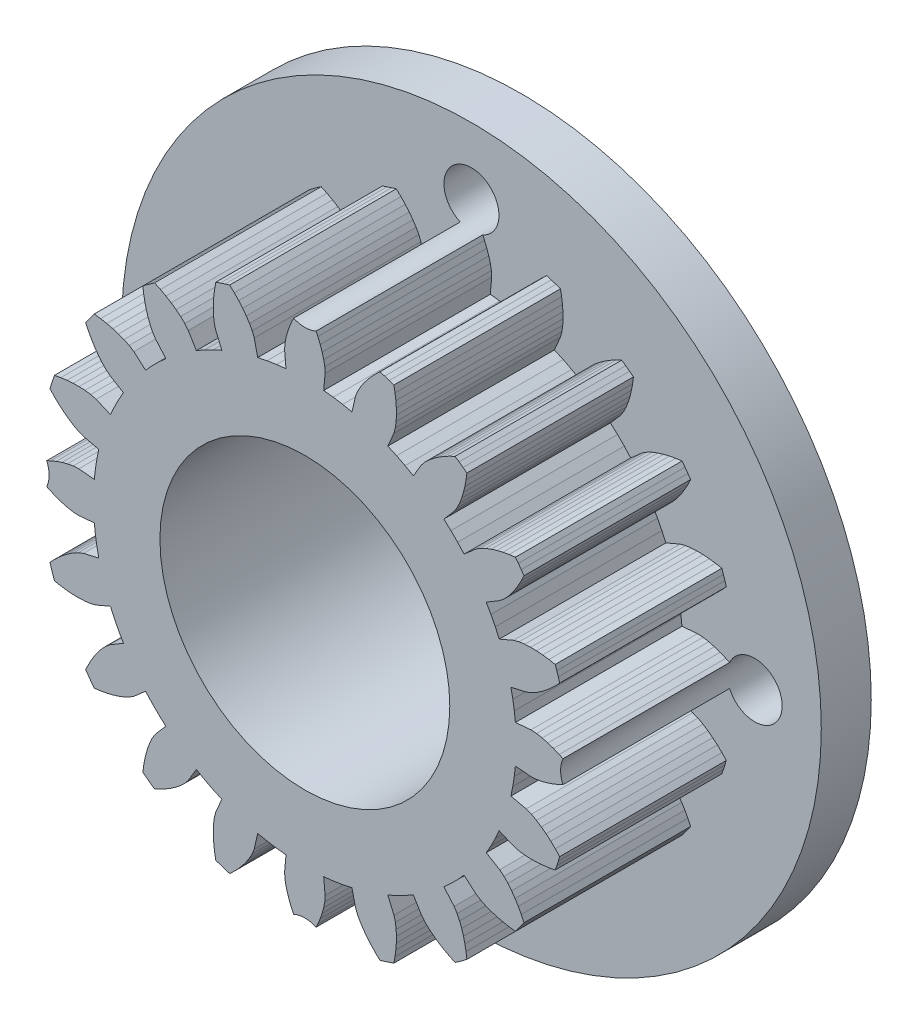
SolidWorks part; units mm, degrees
ref_plane "Спереди" through (0, 0, 0) normal (0, 0, 1) x (1, 0, 0)
ref_plane "Сверху" through (0, 0, 0) normal (0, 1, 0) x (1, 0, 0)
ref_plane "Справа" through (0, 0, 0) normal (1, 0, 0) x (0, 0, -1)
sketch "Эскиз1" plane through (0, 0, 0) normal (0, 0, 1) x (1, 0, 0)
  line L0 (12.6369, -1.1316) -> (13.5712, -1.2152)
  line L1 (13.5712, -1.2152) -> (13.9063, -1.1955)
  line L2 (13.9063, -1.1955) -> (14.2447, -1.1331)
  line L3 (14.2447, -1.1331) -> (14.5846, -1.0409)
  line L4 (14.5846, -1.0409) -> (14.9253, -0.9234)
  line L5 (14.9253, -0.9234) -> (15.2658, -0.7828)
  line L6 (15.2658, -0.7828) -> (15.6056, -0.6206)
  line L7 (15.6056, -0.6206) -> (15.944, -0.4377)
  line L8 (15.944, -0.4377) -> (15.9493, -0.1459)
  line L9 (15.9493, -0.1459) -> (15.9493, 0.1459)
  line L10 (15.9493, 0.1459) -> (15.944, 0.4377)
  line L11 (15.944, 0.4377) -> (15.6056, 0.6206)
  line L12 (15.6056, 0.6206) -> (15.2658, 0.7828)
  line L13 (15.2658, 0.7828) -> (14.9253, 0.9234)
  line L14 (14.9253, 0.9234) -> (14.5846, 1.0409)
  line L15 (14.5846, 1.0409) -> (14.2447, 1.1331)
  line L16 (14.2447, 1.1331) -> (13.9063, 1.1955)
  line L17 (13.9063, 1.1955) -> (13.5712, 1.2152)
  line L18 (13.5712, 1.2152) -> (12.6369, 1.1316)
  line L19 (12.6369, 1.1316) -> (12.5729, 1.7012)
  line L20 (12.5729, 1.7012) -> (12.4833, 2.2673)
  line L21 (12.4833, 2.2673) -> (12.3681, 2.8288)
  line L22 (12.3681, 2.8288) -> (13.2825, 3.038)
  line L23 (13.2825, 3.038) -> (13.5951, 3.1603)
  line L24 (13.5951, 3.1603) -> (13.8976, 3.3242)
  line L25 (13.8976, 3.3242) -> (14.1925, 3.5169)
  line L26 (14.1925, 3.5169) -> (14.4801, 3.7339)
  line L27 (14.4801, 3.7339) -> (14.7606, 3.9729)
  line L28 (14.7606, 3.9729) -> (15.0336, 4.2322)
  line L29 (15.0336, 4.2322) -> (15.2989, 4.5107)
  line L30 (15.2989, 4.5107) -> (15.2138, 4.7898)
  line L31 (15.2138, 4.7898) -> (15.1236, 5.0674)
  line L32 (15.1236, 5.0674) -> (15.0284, 5.3433)
  line L33 (15.0284, 5.3433) -> (14.65, 5.4126)
  line L34 (14.65, 5.4126) -> (14.2767, 5.4619)
  line L35 (14.2767, 5.4619) -> (13.9094, 5.4904)
  line L36 (13.9094, 5.4904) -> (13.5491, 5.4969)
  line L37 (13.5491, 5.4969) -> (13.1974, 5.4795)
  line L38 (13.1974, 5.4795) -> (12.8563, 5.4343)
  line L39 (12.8563, 5.4343) -> (12.5315, 5.3495)
  line L40 (12.5315, 5.3495) -> (11.6688, 4.9812)
  line L41 (11.6688, 4.9812) -> (11.4319, 5.5032)
  line L42 (11.4319, 5.5032) -> (11.1716, 6.0139)
  line L43 (11.1716, 6.0139) -> (10.8886, 6.5123)
  line L44 (10.8886, 6.5123) -> (11.6937, 6.9938)
  line L45 (11.6937, 6.9938) -> (11.9531, 7.2067)
  line L46 (11.9531, 7.2067) -> (12.1902, 7.4561)
  line L47 (12.1902, 7.4561) -> (12.4111, 7.7305)
  line L48 (12.4111, 7.7305) -> (12.6176, 8.0258)
  line L49 (12.6176, 8.0258) -> (12.8104, 8.3397)
  line L50 (12.8104, 8.3397) -> (12.99, 8.6707)
  line L51 (12.99, 8.6707) -> (13.1563, 9.0175)
  line L52 (13.1563, 9.0175) -> (12.9891, 9.2567)
  line L53 (12.9891, 9.2567) -> (12.8175, 9.4928)
  line L54 (12.8175, 9.4928) -> (12.6417, 9.7258)
  line L55 (12.6417, 9.7258) -> (12.2604, 9.6748)
  line L56 (12.2604, 9.6748) -> (11.8902, 9.6063)
  line L57 (11.8902, 9.6063) -> (11.532, 9.5199)
  line L58 (11.532, 9.5199) -> (11.1874, 9.4148)
  line L59 (11.1874, 9.4148) -> (10.8582, 9.2895)
  line L60 (10.8582, 9.2895) -> (10.5477, 9.1411)
  line L61 (10.5477, 9.1411) -> (10.2651, 8.9601)
  line L62 (10.2651, 8.9601) -> (9.5584, 8.3433)
  line L63 (9.5584, 8.3433) -> (9.1718, 8.7665)
  line L64 (9.1718, 8.7665) -> (8.7665, 9.1718)
  line L65 (8.7665, 9.1718) -> (8.3433, 9.5584)
  line L66 (8.3433, 9.5584) -> (8.9601, 10.2651)
  line L67 (8.9601, 10.2651) -> (9.1411, 10.5477)
  line L68 (9.1411, 10.5477) -> (9.2895, 10.8582)
  line L69 (9.2895, 10.8582) -> (9.4148, 11.1874)
  line L70 (9.4148, 11.1874) -> (9.5199, 11.532)
  line L71 (9.5199, 11.532) -> (9.6063, 11.8902)
  line L72 (9.6063, 11.8902) -> (9.6748, 12.2604)
  line L73 (9.6748, 12.2604) -> (9.7258, 12.6417)
  line L74 (9.7258, 12.6417) -> (9.4928, 12.8175)
  line L75 (9.4928, 12.8175) -> (9.2567, 12.9891)
  line L76 (9.2567, 12.9891) -> (9.0175, 13.1563)
  line L77 (9.0175, 13.1563) -> (8.6707, 12.99)
  line L78 (8.6707, 12.99) -> (8.3397, 12.8104)
  line L79 (8.3397, 12.8104) -> (8.0258, 12.6176)
  line L80 (8.0258, 12.6176) -> (7.7305, 12.4111)
  line L81 (7.7305, 12.4111) -> (7.4561, 12.1902)
  line L82 (7.4561, 12.1902) -> (7.2067, 11.9531)
  line L83 (7.2067, 11.9531) -> (6.9938, 11.6937)
  line L84 (6.9938, 11.6937) -> (6.5123, 10.8886)
  line L85 (6.5123, 10.8886) -> (6.0139, 11.1716)
  line L86 (6.0139, 11.1716) -> (5.5032, 11.4319)
  line L87 (5.5032, 11.4319) -> (4.9812, 11.6688)
  line L88 (4.9812, 11.6688) -> (5.3495, 12.5315)
  line L89 (5.3495, 12.5315) -> (5.4343, 12.8563)
  line L90 (5.4343, 12.8563) -> (5.4795, 13.1974)
  line L91 (5.4795, 13.1974) -> (5.4969, 13.5491)
  line L92 (5.4969, 13.5491) -> (5.4904, 13.9094)
  line L93 (5.4904, 13.9094) -> (5.4619, 14.2767)
  line L94 (5.4619, 14.2767) -> (5.4126, 14.65)
  line L95 (5.4126, 14.65) -> (5.3433, 15.0284)
  line L96 (5.3433, 15.0284) -> (5.0674, 15.1236)
  line L97 (5.0674, 15.1236) -> (4.7898, 15.2138)
  line L98 (4.7898, 15.2138) -> (4.5107, 15.2989)
  line L99 (4.5107, 15.2989) -> (4.2322, 15.0336)
  line L100 (4.2322, 15.0336) -> (3.9729, 14.7606)
  line L101 (3.9729, 14.7606) -> (3.7339, 14.4801)
  line L102 (3.7339, 14.4801) -> (3.5169, 14.1925)
  line L103 (3.5169, 14.1925) -> (3.3242, 13.8976)
  line L104 (3.3242, 13.8976) -> (3.1603, 13.5951)
  line L105 (3.1603, 13.5951) -> (3.038, 13.2825)
  line L106 (3.038, 13.2825) -> (2.8288, 12.3681)
  line L107 (2.8288, 12.3681) -> (2.2673, 12.4833)
  line L108 (2.2673, 12.4833) -> (1.7012, 12.5729)
  line L109 (1.7012, 12.5729) -> (1.1316, 12.6369)
  line L110 (1.1316, 12.6369) -> (1.2152, 13.5712)
  line L111 (1.2152, 13.5712) -> (1.1955, 13.9063)
  line L112 (1.1955, 13.9063) -> (1.1331, 14.2447)
  line L113 (1.1331, 14.2447) -> (1.0409, 14.5846)
  line L114 (1.0409, 14.5846) -> (0.9234, 14.9253)
  line L115 (0.9234, 14.9253) -> (0.7828, 15.2658)
  line L116 (0.7828, 15.2658) -> (0.6206, 15.6056)
  line L117 (0.6206, 15.6056) -> (0.4377, 15.944)
  line L118 (0.4377, 15.944) -> (0.1459, 15.9493)
  line L119 (0.1459, 15.9493) -> (-0.1459, 15.9493)
  line L120 (-0.1459, 15.9493) -> (-0.4377, 15.944)
  line L121 (-0.4377, 15.944) -> (-0.6206, 15.6056)
  line L122 (-0.6206, 15.6056) -> (-0.7828, 15.2658)
  line L123 (-0.7828, 15.2658) -> (-0.9234, 14.9253)
  line L124 (-0.9234, 14.9253) -> (-1.0409, 14.5846)
  line L125 (-1.0409, 14.5846) -> (-1.1331, 14.2447)
  line L126 (-1.1331, 14.2447) -> (-1.1955, 13.9063)
  line L127 (-1.1955, 13.9063) -> (-1.2152, 13.5712)
  line L128 (-1.2152, 13.5712) -> (-1.1316, 12.6369)
  line L129 (-1.1316, 12.6369) -> (-1.7012, 12.5729)
  line L130 (-1.7012, 12.5729) -> (-2.2673, 12.4833)
  line L131 (-2.2673, 12.4833) -> (-2.8288, 12.3681)
  line L132 (-2.8288, 12.3681) -> (-3.038, 13.2825)
  line L133 (-3.038, 13.2825) -> (-3.1603, 13.5951)
  line L134 (-3.1603, 13.5951) -> (-3.3242, 13.8976)
  line L135 (-3.3242, 13.8976) -> (-3.5169, 14.1925)
  line L136 (-3.5169, 14.1925) -> (-3.7339, 14.4801)
  line L137 (-3.7339, 14.4801) -> (-3.9729, 14.7606)
  line L138 (-3.9729, 14.7606) -> (-4.2322, 15.0336)
  line L139 (-4.2322, 15.0336) -> (-4.5107, 15.2989)
  line L140 (-4.5107, 15.2989) -> (-4.7898, 15.2138)
  line L141 (-4.7898, 15.2138) -> (-5.0674, 15.1236)
  line L142 (-5.0674, 15.1236) -> (-5.3433, 15.0284)
  line L143 (-5.3433, 15.0284) -> (-5.4126, 14.65)
  line L144 (-5.4126, 14.65) -> (-5.4619, 14.2767)
  line L145 (-5.4619, 14.2767) -> (-5.4904, 13.9094)
  line L146 (-5.4904, 13.9094) -> (-5.4969, 13.5491)
  line L147 (-5.4969, 13.5491) -> (-5.4795, 13.1974)
  line L148 (-5.4795, 13.1974) -> (-5.4343, 12.8563)
  line L149 (-5.4343, 12.8563) -> (-5.3495, 12.5315)
  line L150 (-5.3495, 12.5315) -> (-4.9812, 11.6688)
  line L151 (-4.9812, 11.6688) -> (-5.5032, 11.4319)
  line L152 (-5.5032, 11.4319) -> (-6.0139, 11.1716)
  line L153 (-6.0139, 11.1716) -> (-6.5123, 10.8886)
  line L154 (-6.5123, 10.8886) -> (-6.9938, 11.6937)
  line L155 (-6.9938, 11.6937) -> (-7.2067, 11.9531)
  line L156 (-7.2067, 11.9531) -> (-7.4561, 12.1902)
  line L157 (-7.4561, 12.1902) -> (-7.7305, 12.4111)
  line L158 (-7.7305, 12.4111) -> (-8.0258, 12.6176)
  line L159 (-8.0258, 12.6176) -> (-8.3397, 12.8104)
  line L160 (-8.3397, 12.8104) -> (-8.6707, 12.99)
  line L161 (-8.6707, 12.99) -> (-9.0175, 13.1563)
  line L162 (-9.0175, 13.1563) -> (-9.2567, 12.9891)
  line L163 (-9.2567, 12.9891) -> (-9.4928, 12.8175)
  line L164 (-9.4928, 12.8175) -> (-9.7258, 12.6417)
  line L165 (-9.7258, 12.6417) -> (-9.6748, 12.2604)
  line L166 (-9.6748, 12.2604) -> (-9.6063, 11.8902)
  line L167 (-9.6063, 11.8902) -> (-9.5199, 11.532)
  line L168 (-9.5199, 11.532) -> (-9.4148, 11.1874)
  line L169 (-9.4148, 11.1874) -> (-9.2895, 10.8582)
  line L170 (-9.2895, 10.8582) -> (-9.1411, 10.5477)
  line L171 (-9.1411, 10.5477) -> (-8.9601, 10.2651)
  line L172 (-8.9601, 10.2651) -> (-8.3433, 9.5584)
  line L173 (-8.3433, 9.5584) -> (-8.7665, 9.1718)
  line L174 (-8.7665, 9.1718) -> (-9.1718, 8.7665)
  line L175 (-9.1718, 8.7665) -> (-9.5584, 8.3433)
  line L176 (-9.5584, 8.3433) -> (-10.2651, 8.9601)
  line L177 (-10.2651, 8.9601) -> (-10.5477, 9.1411)
  line L178 (-10.5477, 9.1411) -> (-10.8582, 9.2895)
  line L179 (-10.8582, 9.2895) -> (-11.1874, 9.4148)
  line L180 (-11.1874, 9.4148) -> (-11.532, 9.5199)
  line L181 (-11.532, 9.5199) -> (-11.8902, 9.6063)
  line L182 (-11.8902, 9.6063) -> (-12.2604, 9.6748)
  line L183 (-12.2604, 9.6748) -> (-12.6417, 9.7258)
  line L184 (-12.6417, 9.7258) -> (-12.8175, 9.4928)
  line L185 (-12.8175, 9.4928) -> (-12.9891, 9.2567)
  line L186 (-12.9891, 9.2567) -> (-13.1563, 9.0175)
  line L187 (-13.1563, 9.0175) -> (-12.99, 8.6707)
  line L188 (-12.99, 8.6707) -> (-12.8104, 8.3397)
  line L189 (-12.8104, 8.3397) -> (-12.6176, 8.0258)
  line L190 (-12.6176, 8.0258) -> (-12.4111, 7.7305)
  line L191 (-12.4111, 7.7305) -> (-12.1902, 7.4561)
  line L192 (-12.1902, 7.4561) -> (-11.9531, 7.2067)
  line L193 (-11.9531, 7.2067) -> (-11.6937, 6.9938)
  line L194 (-11.6937, 6.9938) -> (-10.8886, 6.5123)
  line L195 (-10.8886, 6.5123) -> (-11.1716, 6.0139)
  line L196 (-11.1716, 6.0139) -> (-11.4319, 5.5032)
  line L197 (-11.4319, 5.5032) -> (-11.6688, 4.9812)
  line L198 (-11.6688, 4.9812) -> (-12.5315, 5.3495)
  line L199 (-12.5315, 5.3495) -> (-12.8563, 5.4343)
  line L200 (-12.8563, 5.4343) -> (-13.1974, 5.4795)
  line L201 (-13.1974, 5.4795) -> (-13.5491, 5.4969)
  line L202 (-13.5491, 5.4969) -> (-13.9094, 5.4904)
  line L203 (-13.9094, 5.4904) -> (-14.2767, 5.4619)
  line L204 (-14.2767, 5.4619) -> (-14.65, 5.4126)
  line L205 (-14.65, 5.4126) -> (-15.0284, 5.3433)
  line L206 (-15.0284, 5.3433) -> (-15.1236, 5.0674)
  line L207 (-15.1236, 5.0674) -> (-15.2138, 4.7898)
  line L208 (-15.2138, 4.7898) -> (-15.2989, 4.5107)
  line L209 (-15.2989, 4.5107) -> (-15.0336, 4.2322)
  line L210 (-15.0336, 4.2322) -> (-14.7606, 3.9729)
  line L211 (-14.7606, 3.9729) -> (-14.4801, 3.7339)
  line L212 (-14.4801, 3.7339) -> (-14.1925, 3.5169)
  line L213 (-14.1925, 3.5169) -> (-13.8976, 3.3242)
  line L214 (-13.8976, 3.3242) -> (-13.5951, 3.1603)
  line L215 (-13.5951, 3.1603) -> (-13.2825, 3.038)
  line L216 (-13.2825, 3.038) -> (-12.3681, 2.8288)
  line L217 (-12.3681, 2.8288) -> (-12.4833, 2.2673)
  line L218 (-12.4833, 2.2673) -> (-12.5729, 1.7012)
  line L219 (-12.5729, 1.7012) -> (-12.6369, 1.1316)
  line L220 (-12.6369, 1.1316) -> (-13.5712, 1.2152)
  line L221 (-13.5712, 1.2152) -> (-13.9063, 1.1955)
  line L222 (-13.9063, 1.1955) -> (-14.2447, 1.1331)
  line L223 (-14.2447, 1.1331) -> (-14.5846, 1.0409)
  line L224 (-14.5846, 1.0409) -> (-14.9253, 0.9234)
  line L225 (-14.9253, 0.9234) -> (-15.2658, 0.7828)
  line L226 (-15.2658, 0.7828) -> (-15.6056, 0.6206)
  line L227 (-15.6056, 0.6206) -> (-15.944, 0.4377)
  line L228 (-15.944, 0.4377) -> (-15.9493, 0.1459)
  line L229 (-15.9493, 0.1459) -> (-15.9493, -0.1459)
  line L230 (-15.9493, -0.1459) -> (-15.944, -0.4377)
  line L231 (-15.944, -0.4377) -> (-15.6056, -0.6206)
  line L232 (-15.6056, -0.6206) -> (-15.2658, -0.7828)
  line L233 (-15.2658, -0.7828) -> (-14.9253, -0.9234)
  line L234 (-14.9253, -0.9234) -> (-14.5846, -1.0409)
  line L235 (-14.5846, -1.0409) -> (-14.2447, -1.1331)
  line L236 (-14.2447, -1.1331) -> (-13.9063, -1.1955)
  line L237 (-13.9063, -1.1955) -> (-13.5712, -1.2152)
  line L238 (-13.5712, -1.2152) -> (-12.6369, -1.1316)
  line L239 (-12.6369, -1.1316) -> (-12.5729, -1.7012)
  line L240 (-12.5729, -1.7012) -> (-12.4833, -2.2673)
  line L241 (-12.4833, -2.2673) -> (-12.3681, -2.8288)
  line L242 (-12.3681, -2.8288) -> (-13.2825, -3.038)
  line L243 (-13.2825, -3.038) -> (-13.5951, -3.1603)
  line L244 (-13.5951, -3.1603) -> (-13.8976, -3.3242)
  line L245 (-13.8976, -3.3242) -> (-14.1925, -3.5169)
  line L246 (-14.1925, -3.5169) -> (-14.4801, -3.7339)
  line L247 (-14.4801, -3.7339) -> (-14.7606, -3.9729)
  line L248 (-14.7606, -3.9729) -> (-15.0336, -4.2322)
  line L249 (-15.0336, -4.2322) -> (-15.2989, -4.5107)
  line L250 (-15.2989, -4.5107) -> (-15.2138, -4.7898)
  line L251 (-15.2138, -4.7898) -> (-15.1236, -5.0674)
  line L252 (-15.1236, -5.0674) -> (-15.0284, -5.3433)
  line L253 (-15.0284, -5.3433) -> (-14.65, -5.4126)
  line L254 (-14.65, -5.4126) -> (-14.2767, -5.4619)
  line L255 (-14.2767, -5.4619) -> (-13.9094, -5.4904)
  line L256 (-13.9094, -5.4904) -> (-13.5491, -5.4969)
  line L257 (-13.5491, -5.4969) -> (-13.1974, -5.4795)
  line L258 (-13.1974, -5.4795) -> (-12.8563, -5.4343)
  line L259 (-12.8563, -5.4343) -> (-12.5315, -5.3495)
  line L260 (-12.5315, -5.3495) -> (-11.6688, -4.9812)
  line L261 (-11.6688, -4.9812) -> (-11.4319, -5.5032)
  line L262 (-11.4319, -5.5032) -> (-11.1716, -6.0139)
  line L263 (-11.1716, -6.0139) -> (-10.8886, -6.5123)
  line L264 (-10.8886, -6.5123) -> (-11.6937, -6.9938)
  line L265 (-11.6937, -6.9938) -> (-11.9531, -7.2067)
  line L266 (-11.9531, -7.2067) -> (-12.1902, -7.4561)
  line L267 (-12.1902, -7.4561) -> (-12.4111, -7.7305)
  line L268 (-12.4111, -7.7305) -> (-12.6176, -8.0258)
  line L269 (-12.6176, -8.0258) -> (-12.8104, -8.3397)
  line L270 (-12.8104, -8.3397) -> (-12.99, -8.6707)
  line L271 (-12.99, -8.6707) -> (-13.1563, -9.0175)
  line L272 (-13.1563, -9.0175) -> (-12.9891, -9.2567)
  line L273 (-12.9891, -9.2567) -> (-12.8175, -9.4928)
  line L274 (-12.8175, -9.4928) -> (-12.6417, -9.7258)
  line L275 (-12.6417, -9.7258) -> (-12.2604, -9.6748)
  line L276 (-12.2604, -9.6748) -> (-11.8902, -9.6063)
  line L277 (-11.8902, -9.6063) -> (-11.532, -9.5199)
  line L278 (-11.532, -9.5199) -> (-11.1874, -9.4148)
  line L279 (-11.1874, -9.4148) -> (-10.8582, -9.2895)
  line L280 (-10.8582, -9.2895) -> (-10.5477, -9.1411)
  line L281 (-10.5477, -9.1411) -> (-10.2651, -8.9601)
  line L282 (-10.2651, -8.9601) -> (-9.5584, -8.3433)
  line L283 (-9.5584, -8.3433) -> (-9.1718, -8.7665)
  line L284 (-9.1718, -8.7665) -> (-8.7665, -9.1718)
  line L285 (-8.7665, -9.1718) -> (-8.3433, -9.5584)
  line L286 (-8.3433, -9.5584) -> (-8.9601, -10.2651)
  line L287 (-8.9601, -10.2651) -> (-9.1411, -10.5477)
  line L288 (-9.1411, -10.5477) -> (-9.2895, -10.8582)
  line L289 (-9.2895, -10.8582) -> (-9.4148, -11.1874)
  line L290 (-9.4148, -11.1874) -> (-9.5199, -11.532)
  line L291 (-9.5199, -11.532) -> (-9.6063, -11.8902)
  line L292 (-9.6063, -11.8902) -> (-9.6748, -12.2604)
  line L293 (-9.6748, -12.2604) -> (-9.7258, -12.6417)
  line L294 (-9.7258, -12.6417) -> (-9.4928, -12.8175)
  line L295 (-9.4928, -12.8175) -> (-9.2567, -12.9891)
  line L296 (-9.2567, -12.9891) -> (-9.0175, -13.1563)
  line L297 (-9.0175, -13.1563) -> (-8.6707, -12.99)
  line L298 (-8.6707, -12.99) -> (-8.3397, -12.8104)
  line L299 (-8.3397, -12.8104) -> (-8.0258, -12.6176)
  line L300 (-8.0258, -12.6176) -> (-7.7305, -12.4111)
  line L301 (-7.7305, -12.4111) -> (-7.4561, -12.1902)
  line L302 (-7.4561, -12.1902) -> (-7.2067, -11.9531)
  line L303 (-7.2067, -11.9531) -> (-6.9938, -11.6937)
  line L304 (-6.9938, -11.6937) -> (-6.5123, -10.8886)
  line L305 (-6.5123, -10.8886) -> (-6.0139, -11.1716)
  line L306 (-6.0139, -11.1716) -> (-5.5032, -11.4319)
  line L307 (-5.5032, -11.4319) -> (-4.9812, -11.6688)
  line L308 (-4.9812, -11.6688) -> (-5.3495, -12.5315)
  line L309 (-5.3495, -12.5315) -> (-5.4343, -12.8563)
  line L310 (-5.4343, -12.8563) -> (-5.4795, -13.1974)
  line L311 (-5.4795, -13.1974) -> (-5.4969, -13.5491)
  line L312 (-5.4969, -13.5491) -> (-5.4904, -13.9094)
  line L313 (-5.4904, -13.9094) -> (-5.4619, -14.2767)
  line L314 (-5.4619, -14.2767) -> (-5.4126, -14.65)
  line L315 (-5.4126, -14.65) -> (-5.3433, -15.0284)
  line L316 (-5.3433, -15.0284) -> (-5.0674, -15.1236)
  line L317 (-5.0674, -15.1236) -> (-4.7898, -15.2138)
  line L318 (-4.7898, -15.2138) -> (-4.5107, -15.2989)
  line L319 (-4.5107, -15.2989) -> (-4.2322, -15.0336)
  line L320 (-4.2322, -15.0336) -> (-3.9729, -14.7606)
  line L321 (-3.9729, -14.7606) -> (-3.7339, -14.4801)
  line L322 (-3.7339, -14.4801) -> (-3.5169, -14.1925)
  line L323 (-3.5169, -14.1925) -> (-3.3242, -13.8976)
  line L324 (-3.3242, -13.8976) -> (-3.1603, -13.5951)
  line L325 (-3.1603, -13.5951) -> (-3.038, -13.2825)
  line L326 (-3.038, -13.2825) -> (-2.8288, -12.3681)
  line L327 (-2.8288, -12.3681) -> (-2.2673, -12.4833)
  line L328 (-2.2673, -12.4833) -> (-1.7012, -12.5729)
  line L329 (-1.7012, -12.5729) -> (-1.1316, -12.6369)
  line L330 (-1.1316, -12.6369) -> (-1.2152, -13.5712)
  line L331 (-1.2152, -13.5712) -> (-1.1955, -13.9063)
  line L332 (-1.1955, -13.9063) -> (-1.1331, -14.2447)
  line L333 (-1.1331, -14.2447) -> (-1.0409, -14.5846)
  line L334 (-1.0409, -14.5846) -> (-0.9234, -14.9253)
  line L335 (-0.9234, -14.9253) -> (-0.7828, -15.2658)
  line L336 (-0.7828, -15.2658) -> (-0.6206, -15.6056)
  line L337 (-0.6206, -15.6056) -> (-0.4377, -15.944)
  line L338 (-0.4377, -15.944) -> (-0.1459, -15.9493)
  line L339 (-0.1459, -15.9493) -> (0.1459, -15.9493)
  line L340 (0.1459, -15.9493) -> (0.4377, -15.944)
  line L341 (0.4377, -15.944) -> (0.6206, -15.6056)
  line L342 (0.6206, -15.6056) -> (0.7828, -15.2658)
  line L343 (0.7828, -15.2658) -> (0.9234, -14.9253)
  line L344 (0.9234, -14.9253) -> (1.0409, -14.5846)
  line L345 (1.0409, -14.5846) -> (1.1331, -14.2447)
  line L346 (1.1331, -14.2447) -> (1.1955, -13.9063)
  line L347 (1.1955, -13.9063) -> (1.2152, -13.5712)
  line L348 (1.2152, -13.5712) -> (1.1316, -12.6369)
  line L349 (1.1316, -12.6369) -> (1.7012, -12.5729)
  line L350 (1.7012, -12.5729) -> (2.2673, -12.4833)
  line L351 (2.2673, -12.4833) -> (2.8288, -12.3681)
  line L352 (2.8288, -12.3681) -> (3.038, -13.2825)
  line L353 (3.038, -13.2825) -> (3.1603, -13.5951)
  line L354 (3.1603, -13.5951) -> (3.3242, -13.8976)
  line L355 (3.3242, -13.8976) -> (3.5169, -14.1925)
  line L356 (3.5169, -14.1925) -> (3.7339, -14.4801)
  line L357 (3.7339, -14.4801) -> (3.9729, -14.7606)
  line L358 (3.9729, -14.7606) -> (4.2322, -15.0336)
  line L359 (4.2322, -15.0336) -> (4.5107, -15.2989)
  line L360 (4.5107, -15.2989) -> (4.7898, -15.2138)
  line L361 (4.7898, -15.2138) -> (5.0674, -15.1236)
  line L362 (5.0674, -15.1236) -> (5.3433, -15.0284)
  line L363 (5.3433, -15.0284) -> (5.4126, -14.65)
  line L364 (5.4126, -14.65) -> (5.4619, -14.2767)
  line L365 (5.4619, -14.2767) -> (5.4904, -13.9094)
  line L366 (5.4904, -13.9094) -> (5.4969, -13.5491)
  line L367 (5.4969, -13.5491) -> (5.4795, -13.1974)
  line L368 (5.4795, -13.1974) -> (5.4343, -12.8563)
  line L369 (5.4343, -12.8563) -> (5.3495, -12.5315)
  line L370 (5.3495, -12.5315) -> (4.9812, -11.6688)
  line L371 (4.9812, -11.6688) -> (5.5032, -11.4319)
  line L372 (5.5032, -11.4319) -> (6.0139, -11.1716)
  line L373 (6.0139, -11.1716) -> (6.5123, -10.8886)
  line L374 (6.5123, -10.8886) -> (6.9938, -11.6937)
  line L375 (6.9938, -11.6937) -> (7.2067, -11.9531)
  line L376 (7.2067, -11.9531) -> (7.4561, -12.1902)
  line L377 (7.4561, -12.1902) -> (7.7305, -12.4111)
  line L378 (7.7305, -12.4111) -> (8.0258, -12.6176)
  line L379 (8.0258, -12.6176) -> (8.3397, -12.8104)
  line L380 (8.3397, -12.8104) -> (8.6707, -12.99)
  line L381 (8.6707, -12.99) -> (9.0175, -13.1563)
  line L382 (9.0175, -13.1563) -> (9.2567, -12.9891)
  line L383 (9.2567, -12.9891) -> (9.4928, -12.8175)
  line L384 (9.4928, -12.8175) -> (9.7258, -12.6417)
  line L385 (9.7258, -12.6417) -> (9.6748, -12.2604)
  line L386 (9.6748, -12.2604) -> (9.6063, -11.8902)
  line L387 (9.6063, -11.8902) -> (9.5199, -11.532)
  line L388 (9.5199, -11.532) -> (9.4148, -11.1874)
  line L389 (9.4148, -11.1874) -> (9.2895, -10.8582)
  line L390 (9.2895, -10.8582) -> (9.1411, -10.5477)
  line L391 (9.1411, -10.5477) -> (8.9601, -10.2651)
  line L392 (8.9601, -10.2651) -> (8.3433, -9.5584)
  line L393 (8.3433, -9.5584) -> (8.7665, -9.1718)
  line L394 (8.7665, -9.1718) -> (9.1718, -8.7665)
  line L395 (9.1718, -8.7665) -> (9.5584, -8.3433)
  line L396 (9.5584, -8.3433) -> (10.2651, -8.9601)
  line L397 (10.2651, -8.9601) -> (10.5477, -9.1411)
  line L398 (10.5477, -9.1411) -> (10.8582, -9.2895)
  line L399 (10.8582, -9.2895) -> (11.1874, -9.4148)
  line L400 (11.1874, -9.4148) -> (11.532, -9.5199)
  line L401 (11.532, -9.5199) -> (11.8902, -9.6063)
  line L402 (11.8902, -9.6063) -> (12.2604, -9.6748)
  line L403 (12.2604, -9.6748) -> (12.6417, -9.7258)
  line L404 (12.6417, -9.7258) -> (12.8175, -9.4928)
  line L405 (12.8175, -9.4928) -> (12.9891, -9.2567)
  line L406 (12.9891, -9.2567) -> (13.1563, -9.0175)
  line L407 (13.1563, -9.0175) -> (12.99, -8.6707)
  line L408 (12.99, -8.6707) -> (12.8104, -8.3397)
  line L409 (12.8104, -8.3397) -> (12.6176, -8.0258)
  line L410 (12.6176, -8.0258) -> (12.4111, -7.7305)
  line L411 (12.4111, -7.7305) -> (12.1902, -7.4561)
  line L412 (12.1902, -7.4561) -> (11.9531, -7.2067)
  line L413 (11.9531, -7.2067) -> (11.6937, -6.9938)
  line L414 (11.6937, -6.9938) -> (10.8886, -6.5123)
  line L415 (10.8886, -6.5123) -> (11.1716, -6.0139)
  line L416 (11.1716, -6.0139) -> (11.4319, -5.5032)
  line L417 (11.4319, -5.5032) -> (11.6688, -4.9812)
  line L418 (11.6688, -4.9812) -> (12.5315, -5.3495)
  line L419 (12.5315, -5.3495) -> (12.8563, -5.4343)
  line L420 (12.8563, -5.4343) -> (13.1974, -5.4795)
  line L421 (13.1974, -5.4795) -> (13.5491, -5.4969)
  line L422 (13.5491, -5.4969) -> (13.9094, -5.4904)
  line L423 (13.9094, -5.4904) -> (14.2767, -5.4619)
  line L424 (14.2767, -5.4619) -> (14.65, -5.4126)
  line L425 (14.65, -5.4126) -> (15.0284, -5.3433)
  line L426 (15.0284, -5.3433) -> (15.1236, -5.0674)
  line L427 (15.1236, -5.0674) -> (15.2138, -4.7898)
  line L428 (15.2138, -4.7898) -> (15.2989, -4.5107)
  line L429 (15.2989, -4.5107) -> (15.0336, -4.2322)
  line L430 (15.0336, -4.2322) -> (14.7606, -3.9729)
  line L431 (14.7606, -3.9729) -> (14.4801, -3.7339)
  line L432 (14.4801, -3.7339) -> (14.1925, -3.5169)
  line L433 (14.1925, -3.5169) -> (13.8976, -3.3242)
  line L434 (13.8976, -3.3242) -> (13.5951, -3.1603)
  line L435 (13.5951, -3.1603) -> (13.2825, -3.038)
  line L436 (13.2825, -3.038) -> (12.3681, -2.8288)
  line L437 (12.3681, -2.8288) -> (12.4833, -2.2673)
  line L438 (12.4833, -2.2673) -> (12.5729, -1.7012)
  line L439 (12.5729, -1.7012) -> (12.6369, -1.1316)
  circle A0 centre (0, 0) radius 8.7
extrude "Sun_teeth" add sketch "Эскиз1" along normal blind 10 from offset 30
sketch "Эскиз2" plane through (0, 0, 0) normal (0, 0, 1) x (1, 0, 0)
  circle A0 centre (0, 0) radius 21
  circle A1 centre (0, 0) radius 8.7
extrude "Sun_flange" add sketch "Эскиз2" along normal blind 3 from offset 27
sketch "Эскиз3" plane through (0, 0, 0) normal (0, 0, 1) x (1, 0, 0)
  circle A0 centre (17, 0) radius 1.65
  circle A1 centre (0, 17) radius 1.65
  circle A2 centre (-17, 0) radius 1.65
  circle A3 centre (0, -17) radius 1.65
extrude "Through_holes" cut sketch "Эскиз3" against normal mid plane 200
